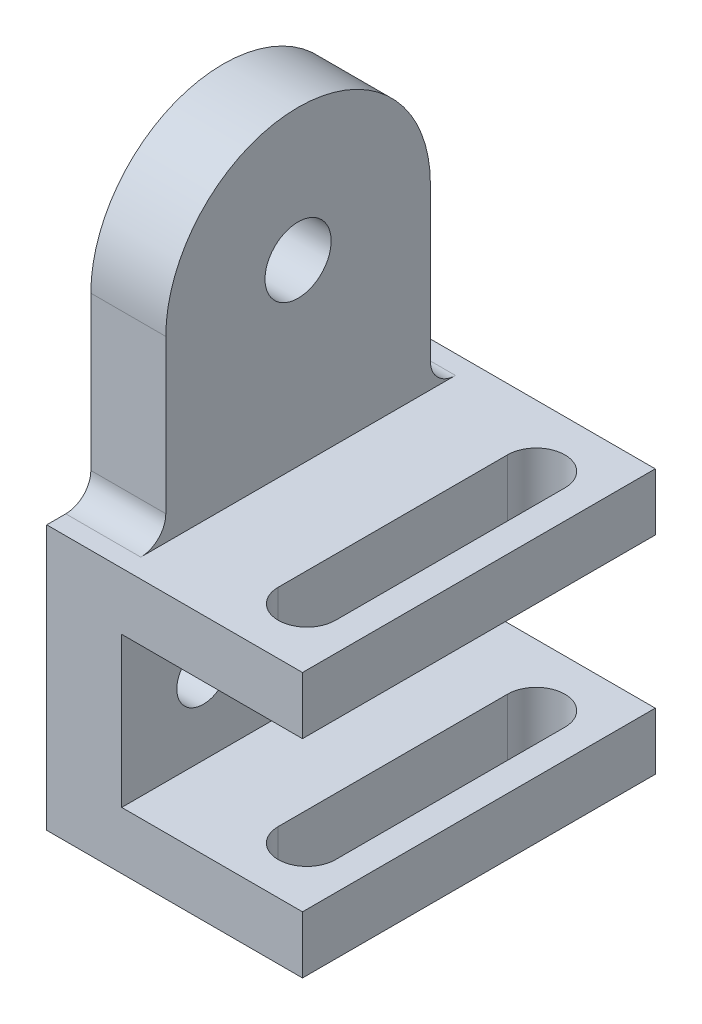
SolidWorks part; units mm, degrees
ref_plane "Front Plane" through (0, 0, 0) normal (0, 0, 1) x (1, 0, 0)
ref_plane "Top Plane" through (0, 0, 0) normal (0, 1, 0) x (1, 0, 0)
ref_plane "Right Plane" through (0, 0, 0) normal (1, 0, 0) x (0, 0, -1)
sketch "Sketch1" plane through (0, 0, 0) normal (0, 0, 1) x (1, 0, 0)
  line L0 (-12, 17) -> (-12, -17)
  line L1 (-29, 30) -> (29, 30)
  line L2 (-29, 30) -> (-29, -30)
  line L3 (-29, -30) -> (29, -30)
  line L4 (29, 30) -> (29, 17)
  line L5 (-12, 17) -> (29, 17)
  line L6 (-12, -17) -> (29, -17)
  line L7 (29, -17) -> (29, -30)
  line L8 (-29, 17) -> (29, 17) construction
  line L9 (-12, 30) -> (-12, -30) construction
  line L10 (-29, -17) -> (29, -17) construction
  point P0 (0, 0)
  dimension "D4" = 29
  dimension "D5" = 29
  dimension "D6" = 30
  dimension "D7" = 30
  dimension "D1" = 17
  dimension "D2" = 13
  dimension "D3" = 13
extrude "Boss-Extrude1" add sketch "Sketch1" against normal blind 80
sketch "Sketch2" plane through (-29, 0, 0) normal (-1, 0, 0) x (0, 0, 1)
  line L1 (0, 30) -> (0, -30) construction
  line L4 (-80, -30) -> (0, -30) construction
  line L5 (-70, 70.5) -> (-70, 35.6839)
  line L6 (-80, 30) -> (0, 30) construction
  line L7 (-10, 70.5) -> (-10, 35.6839)
  line L8 (-80, 30) -> (-4.3161, 30)
  line L9 (-4.3161, 30) -> (0, 30)
  line L11 (-75.6839, 30) -> (-4.3161, 30)
  circle A0 centre (-40, 70.5) radius 7.5
  arc A1 (-10, 70.5) -> (-70, 70.5) centre (-40, 70.5) ccw
  arc A2 (-75.6839, 30) -> (-70, 35.6839) centre (-75.6839, 35.6839) ccw
  arc A3 (-4.3161, 30) -> (-10, 35.6839) centre (-4.3161, 35.6839) cw
  point P20 (-70, 30)
  point P21 (-10, 30)
  dimension "D1" = 60
  dimension "D2" = 15
  dimension "D5" = 5.6839
  dimension "D6" = 5.6839
  dimension "D3" = 40
  dimension "D4" = 100.5
extrude "Boss-Extrude2" add sketch "Sketch2" against normal blind 17 contours L11 A2 L5 A1 L7 A3
sketch "Sketch3" plane through (-29, 0, 0) normal (-1, 0, 0) x (0, 0, 1)
  circle A0 centre (-40, 70.5) radius 7.5
  dimension "D1" = 15
extrude "Cut-Extrude1" cut sketch "Sketch3" against normal blind 17
sketch "Sketch4" plane through (0, 30, 0) normal (0, 1, 0) x (1, 0, 0)
  line L0 (29, 0) -> (-29, 0) construction
  line L5 (9.5, 66) -> (9.5, 14)
  line L6 (22.5, 66) -> (22.5, 14)
  line L8 (29, 80) -> (29, 0) construction
  arc A0 (22.5, 66) -> (9.5, 66) centre (16, 66) ccw
  arc A1 (9.5, 14) -> (22.5, 14) centre (16, 14) ccw
  dimension "D1" = 13
  dimension "D2" = 13
  dimension "D3" = 52
  dimension "D4" = 14
  dimension "D5" = 13
  dimension "D6" = 22.5
extrude "Cut-Extrude2" cut sketch "Sketch4" against normal blind 70
sketch "Sketch6" plane through (-12, 0, 0) normal (1, 0, 0) x (0, 0, -1)
  line L0 (80, -30) -> (80, -17) construction
  line L1 (0, -30) -> (0, -17) construction
  line L2 (80, -30) -> (0, -30) construction
  circle A0 centre (18.5, 0) radius 6
  circle A1 centre (61.5, 0) radius 6
  dimension "D1" = 12
  dimension "D2" = 12
  dimension "D3" = 43
  dimension "D4" = 18.5
  dimension "D5" = 18.5
  dimension "D6" = 30
extrude "Cut-Extrude3" cut sketch "Sketch6" against normal blind 20
